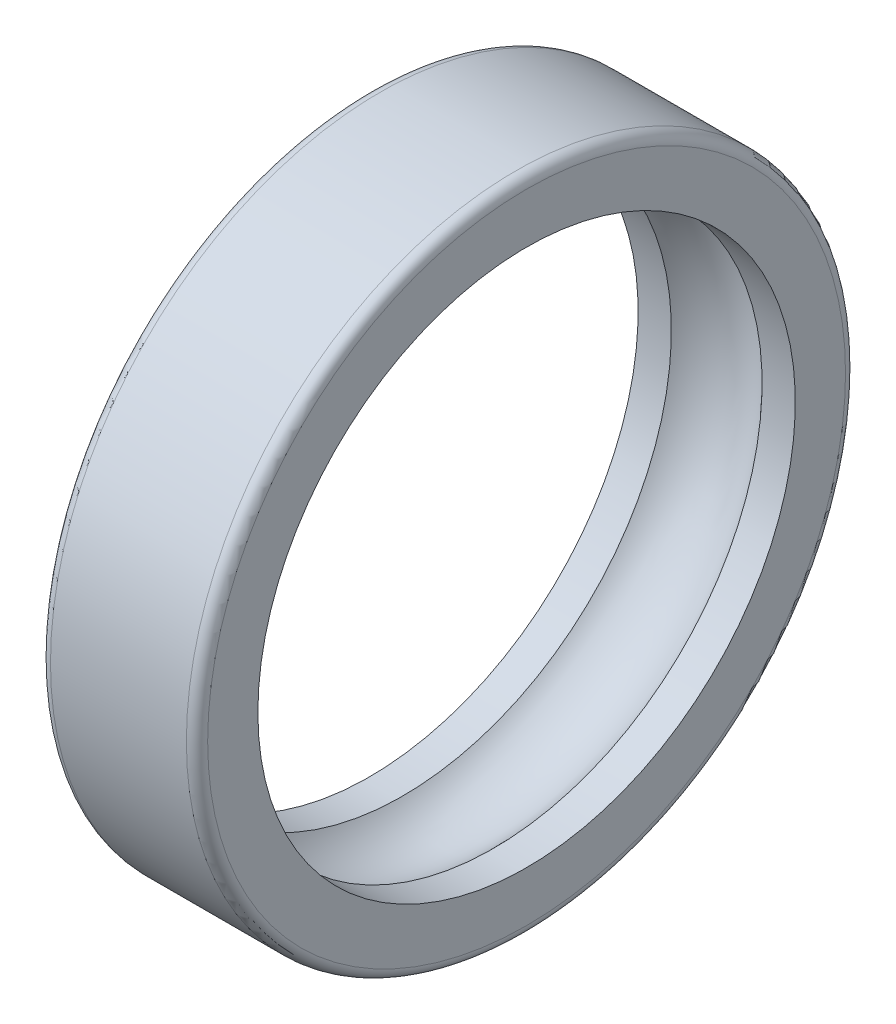
SolidWorks part; units mm, degrees
ref_plane "Plan de face" through (0, 0, 0) normal (0, 0, 1) x (1, 0, 0)
ref_plane "Plan de dessus" through (0, 0, 0) normal (0, 1, 0) x (1, 0, 0)
ref_plane "Plan de droite" through (0, 0, 0) normal (1, 0, 0) x (0, 0, -1)
sketch "Esquisse2" plane through (0, 0, 0) normal (0, 0, 1) x (1, 0, 0)
  line L0 (-31.3648, 0) -> (31.3648, 0) construction
  line L1 (0, 0) -> (0, 53) construction
  line L2 (-15.5, 53) -> (-8.9443, 53)
  line L3 (-15.5, 53) -> (-15.5, 65)
  line L4 (-15.5, 65) -> (15.5, 65)
  line L5 (15.5, 53) -> (15.5, 65)
  line L6 (-15.5, 53) -> (15.5, 65) construction
  line L7 (-15.5, 65) -> (15.5, 53) construction
  line L8 (8.9443, 53) -> (15.5, 53)
  arc A0 (-8.9443, 53) -> (8.9443, 53) centre (0, 45) cw
  point P0 (0, 59)
  point P4 (0, 0)
  dimension "D5" = 12
  dimension "D1" = 31
  dimension "D2" = 53
  dimension "D3" = 65
  dimension "D4" = 8
revolve "Révolution1" add sketch "Esquisse2" angle 360 about L0
fillet "Congé1" radius 2.1 2 edges at (15.5, 0, 65) (-15.5, 0, 65)
